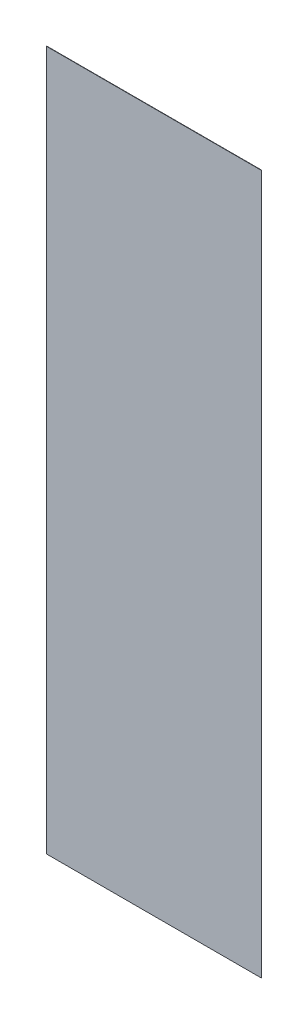
SolidWorks part; units mm, degrees
ref_plane "Alzado" through (0, 0, 0) normal (0, 0, 1) x (1, 0, 0)
ref_plane "Planta" through (0, 0, 0) normal (0, 1, 0) x (1, 0, 0)
ref_plane "Vista lateral" through (0, 0, 0) normal (1, 0, 0) x (0, 0, -1)
sketch "Croquis1" plane through (0, 0, 0) normal (0, 0, 1) x (1, 0, 0)
  line L1 (0, 0) -> (750, 0)
  line L2 (0, 0) -> (0, -2440)
  line L3 (0, -2440) -> (750, -2440)
  line L4 (750, 0) -> (750, -2440)
  dimension "D1" = 2440
  dimension "D2" = 750
extrude "Saliente-Extruir1" add sketch "Croquis1" along normal blind 1.21
